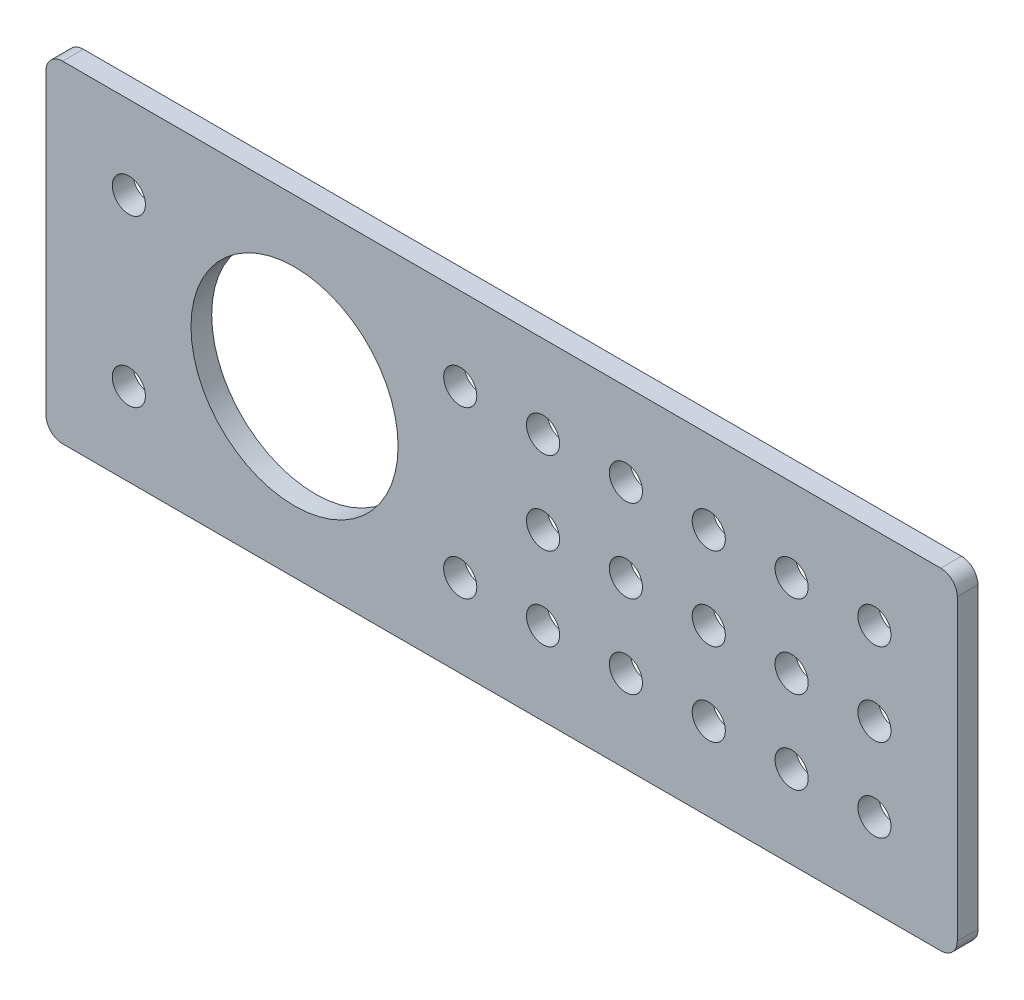
SolidWorks part; units mm, degrees
ref_plane "Front Plane" through (0, 0, 0) normal (0, 0, 1) x (1, 0, 0)
ref_plane "Top Plane" through (0, 0, 0) normal (0, 1, 0) x (1, 0, 0)
ref_plane "Right Plane" through (0, 0, 0) normal (1, 0, 0) x (0, 0, -1)
sketch "Sketch1" plane through (0, 0, 0) normal (0, 0, 1) x (1, 0, 0)
  arc A19 (-480.6, -14.2) -> (-459.2, -14.2) centre (-469.9, 0) ccw
  arc A20 (-446.9968, 12.573) -> (-442.0032, 12.573) centre (-444.5, 12.7) ccw
  arc A21 (-421.5968, 12.573) -> (-416.6032, 12.573) centre (-419.1, 12.7) ccw
  arc A22 (-434.2968, 12.573) -> (-429.3032, 12.573) centre (-431.8, 12.7) ccw
  arc A23 (-434.2968, -0.127) -> (-429.3032, -0.127) centre (-431.8, 0) ccw
  arc A24 (-421.5968, -0.127) -> (-416.6032, -0.127) centre (-419.1, 0) ccw
  arc A25 (-421.5968, -12.827) -> (-416.6032, -12.827) centre (-419.1, -12.7) ccw
  arc A26 (-434.2968, -12.827) -> (-429.3032, -12.827) centre (-431.8, -12.7) ccw
  arc A27 (-446.9968, -12.827) -> (-442.0032, -12.827) centre (-444.5, -12.7) ccw
  arc A28 (-491.5572, 0.127) -> (-494.0059, 2.139) centre (-493.7125, 0) ccw
  arc A29 (-494.0059, -2.139) -> (-491.5572, -0.127) centre (-493.7125, 0) ccw
  arc A30 (-497.7968, 12.573) -> (-492.8032, 12.573) centre (-495.3, 12.7) ccw
  arc A31 (-497.7968, -12.827) -> (-492.8032, -12.827) centre (-495.3, -12.7) ccw
  circle A32 centre (-481.8062, -20.6222) radius 2.159
  circle A33 centre (-457.9938, -20.6222) radius 2.159
  arc A34 (-448.2428, -0.127) -> (-445.7941, -2.139) centre (-446.0875, 0) ccw
  arc A35 (-445.7941, 2.139) -> (-448.2428, 0.127) centre (-446.0875, 0) ccw
  circle A36 centre (-457.9937, 20.6222) radius 2.159
  circle A37 centre (-481.8063, 20.6222) radius 2.159
sketch "Sketch2" plane through (0, 0, 0) normal (0, 0, 1) x (1, 0, 0)
  line L0 (-508, 25.4) -> (-481.6246, 25.4)
  line L1 (-481.6246, 25.4) -> (-457.9938, 25.4)
  line L2 (-457.9938, 25.4) -> (-431.8, 25.4)
  line L3 (-431.8, 25.4) -> (-368.3, 25.4)
  line L4 (-368.3, 25.4) -> (-368.3, -25.4)
  line L5 (-368.3, -25.4) -> (-431.8, -25.4)
  line L6 (-431.8, -25.4) -> (-457.9938, -25.4)
  line L7 (-457.9938, -25.4) -> (-481.6246, -25.4)
  line L8 (-481.6246, -25.4) -> (-508, -25.4)
  line L9 (-508, 25.4) -> (-508, -25.4)
  line L10 (-419.1, 12.7) -> (-406.4, 12.7) construction
  circle A0 centre (-469.9, 0) radius 15.875
  circle A7 centre (-495.3, 12.7) radius 2.54
  circle A8 centre (-495.3, -12.7) radius 2.54
  circle A9 centre (-444.5, -12.7) radius 2.54
  circle A10 centre (-431.8, -12.7) radius 2.54
  circle A11 centre (-419.1, -12.7) radius 2.54
  circle A12 centre (-419.1, 0) radius 2.54
  circle A13 centre (-431.8, 0) radius 2.54
  circle A14 centre (-431.8, 12.7) radius 2.54
  circle A15 centre (-419.1, 12.7) radius 2.54
  circle A16 centre (-444.5, 12.7) radius 2.54
  circle A17 centre (-406.4, 12.7) radius 2.54
  circle A18 centre (-406.4, 0) radius 2.54
  circle A19 centre (-406.4, -12.7) radius 2.54
  circle A20 centre (-393.7, 12.7) radius 2.54
  circle A21 centre (-393.7, 0) radius 2.54
  circle A22 centre (-393.7, -12.7) radius 2.54
  circle A23 centre (-381, 12.7) radius 2.54
  circle A24 centre (-381, 0) radius 2.54
  circle A25 centre (-381, -12.7) radius 2.54
  point P64 (0, 0)
  dimension "D2" = 31.75
  dimension "D3" = 5.08
  dimension "D4" = 50.8
  dimension "D5" = 25.4
  dimension "D8" = 38.1
  dimension "D9" = 38.1
  dimension "D11" = 12.7
  dimension "D12" = 101.6
  dimension "D13" = 50.8
  dimension "D10" = 4
extrude "Boss-Extrude1" add sketch "Sketch2" along normal blind 3.175
fillet "Fillet1" radius 2.54 4 edges at (-368.3, 25.4, 1.5875) (-368.3, -25.4, 1.5875) (-508, -25.4, 1.5875) (-508, 25.4, 1.5875)
